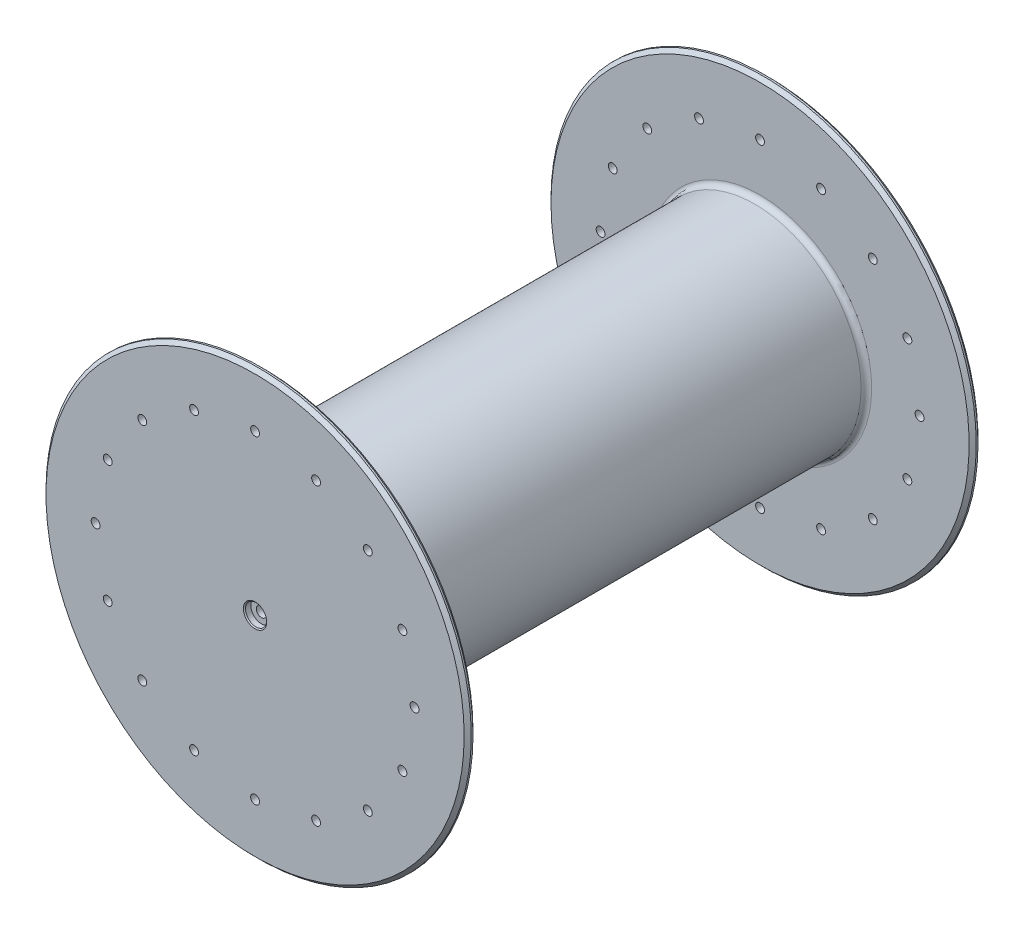
SolidWorks part; units mm, degrees
ref_plane "Front Plane" through (0, 0, 0) normal (0, 0, 1) x (1, 0, 0)
ref_plane "Top Plane" through (0, 0, 0) normal (0, 1, 0) x (1, 0, 0)
ref_plane "Right Plane" through (0, 0, 0) normal (1, 0, 0) x (0, 0, -1)
sketch "Sketch1" plane through (0, 0, 0) normal (0, 0, 1) x (1, 0, 0)
  circle A0 centre (0, 0) radius 60
  dimension "ShaftDiameter " = 120
extrude "Boss-Extrude1" add sketch "Sketch1" along normal mid plane 280
sketch "Sketch2" plane through (0, 0, 140) normal (0, 0, 1) x (1, 0, 0)
  circle A0 centre (0, 0) radius 120
  dimension "D1" = 240
extrude "Boss-Extrude2" add sketch "Sketch2" along normal blind 5
chamfer "Chamfer1" distance 2 angle 45 2 edges at (120, 0, 140) (120, 0, 145)
sketch "Sketch3" plane through (0, 0, 145) normal (0, 0, 1) x (1, 0, 0)
  line L0 (0, 120) -> (0, 60) construction
  circle A2 centre (0, 0) radius 120 construction
  circle A3 centre (0, 0) radius 60 construction
  circle A4 centre (0, 90) radius 2.5
  dimension "D1" = 5
extrude "Cut-Extrude1" cut sketch "Sketch3" against normal through all
pattern_circular "CirPattern1" count 16 over 360 about axis through (0, 0, 140) along (0, 0, 1) of "Cut-Extrude1"
fillet "Fillet1" radius 3 1 edges at (60, 0, 140)
hole_wizard "CBORE for #12 Binding Head Machine Screw1" positions "Sketch6" profile "Sketch7" counterbore size "#12" standard "ANSI Inch" end condition through all
sketch "Sketch6" plane through (0, 0, 145) normal (0, 0, 1) x (1, 0, 0)
  point P0 (0, 0)
sketch "Sketch7" plane through (0, 0, 145) normal (1, 0, 0) x (0, -1, 0)
  line L0 (0, 0) -> (0, 290)
  line L1 (0, 290) -> (2.8956, 290)
  line L3 (2.8956, 290) -> (2.8956, 3.5814)
  line L4 (5.9538, 3.5814) -> (2.8956, 3.5814)
  line L5 (5.9538, 3.5814) -> (5.9538, 0.5328)
  line L6 (5.9538, 0.5328) -> (6.5888, 0)
  line L7 (6.5888, 0) -> (0, 0)
  line L8 (-5.9538, 0.5328) -> (-6.5888, 0) construction
  line L11 (0, -6.35) -> (0, 107.95) construction
  dimension "Thru Hole Dia." = 5.7912
  dimension "Thru Hole Depth" = 290
  dimension "C'Bore Dia." = 11.9075
  dimension "C'Bore Depth" = 3.5814
  dimension "Near C'Sink Dia." = 13.1775
  dimension "Near C'Sink Angle" = 100
mirror "Mirror1" about plane through (0, 0, 0) normal (0, 0, 1) of "CBORE for #12 Binding Head Machine Screw1", "Fillet1", "Cut-Extrude1", "Boss-Extrude2", "Chamfer1", "CirPattern1"
